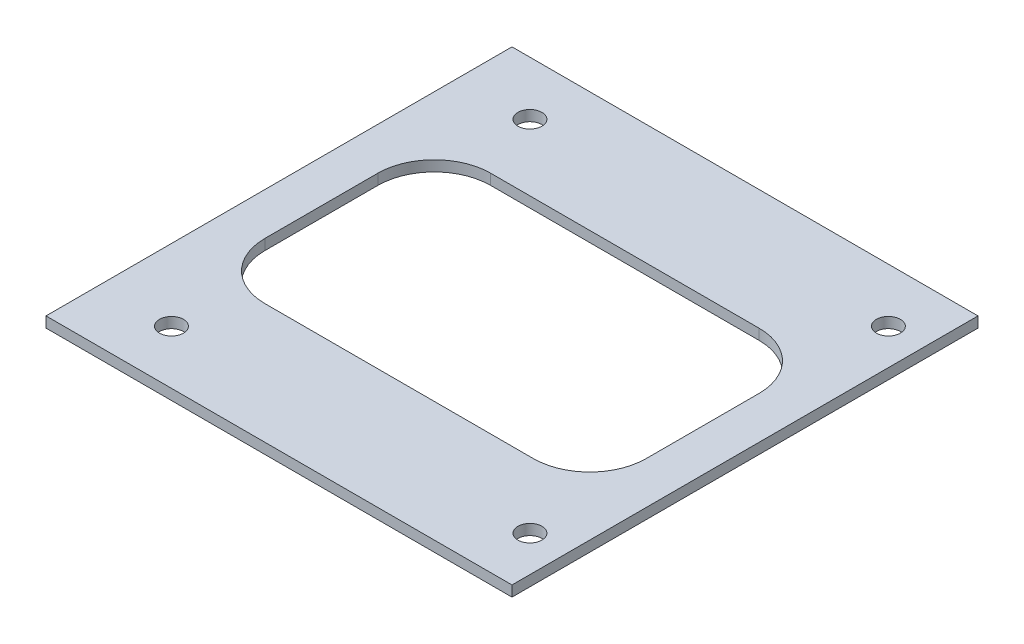
SolidWorks part; units mm, degrees
ref_plane "Front" through (0, 0, 0) normal (0, 0, 1) x (1, 0, 0)
ref_plane "Top" through (0, 0, 0) normal (0, 1, 0) x (1, 0, 0)
ref_plane "Right" through (0, 0, 0) normal (1, 0, 0) x (0, 0, -1)
sketch "Sketch1" plane through (0, 0, 0) normal (0, 1, 0) x (1, 0, 0)
  line L1 (-82.55, 82.55) -> (82.55, 82.55)
  line L2 (-82.55, 82.55) -> (-82.55, -82.55)
  line L3 (-82.55, -82.55) -> (82.55, -82.55)
  line L4 (82.55, 82.55) -> (82.55, -82.55)
  line L5 (-82.55, 82.55) -> (82.55, -82.55) construction
  line L6 (-82.55, -82.55) -> (82.55, 82.55) construction
  point P0 (0, 0)
  dimension "D1" = 165.1
  dimension "D2" = 165.1
extrude "Boss-Extrude1" add sketch "Sketch1" along normal blind 3.75
sketch "Sketch2" plane through (0, 3.75, 0) normal (0, 1, 0) x (1, 0, 0)
  circle A0 centre (69.85, 63.5) radius 4.25
  circle A1 centre (-57.15, 63.5) radius 4.25
  circle A2 centre (-57.15, -63.5) radius 4.25
  circle A3 centre (69.85, -63.5) radius 4.25
  dimension "D1" = 8.5
extrude "Cut-Extrude1" cut sketch "Sketch2" against normal up to next
sketch "Sketch3" plane through (0, 0, 0) normal (0, -1, 0) x (1, 0, 0)
  line L0 (-67.55, -20) -> (-67.55, 20) construction
  line L1 (-47.55, 40) -> (47.55, 40) construction
  line L2 (67.55, 20) -> (67.55, -20) construction
  line L3 (47.55, -40) -> (-47.55, -40) construction
  line L4 (-67.55, -20) -> (-67.55, 20)
  line L5 (-47.55, 40) -> (47.55, 40)
  line L6 (67.55, 20) -> (67.55, -20)
  line L7 (47.55, -40) -> (-47.55, -40)
  arc A0 (-67.55, -20) -> (-47.55, -40) centre (-47.55, -20) ccw construction
  arc A1 (-47.55, 40) -> (-67.55, 20) centre (-47.55, 20) ccw construction
  arc A2 (67.55, 20) -> (47.55, 40) centre (47.55, 20) ccw construction
  arc A3 (47.55, -40) -> (67.55, -20) centre (47.55, -20) ccw construction
  arc A4 (-67.55, -20) -> (-47.55, -40) centre (-47.55, -20) ccw
  arc A5 (-47.55, 40) -> (-67.55, 20) centre (-47.55, 20) ccw
  arc A6 (67.55, 20) -> (47.55, 40) centre (47.55, 20) ccw
  arc A7 (47.55, -40) -> (67.55, -20) centre (47.55, -20) ccw
extrude "Cut-Extrude2" cut sketch "Sketch3" against normal up to next
